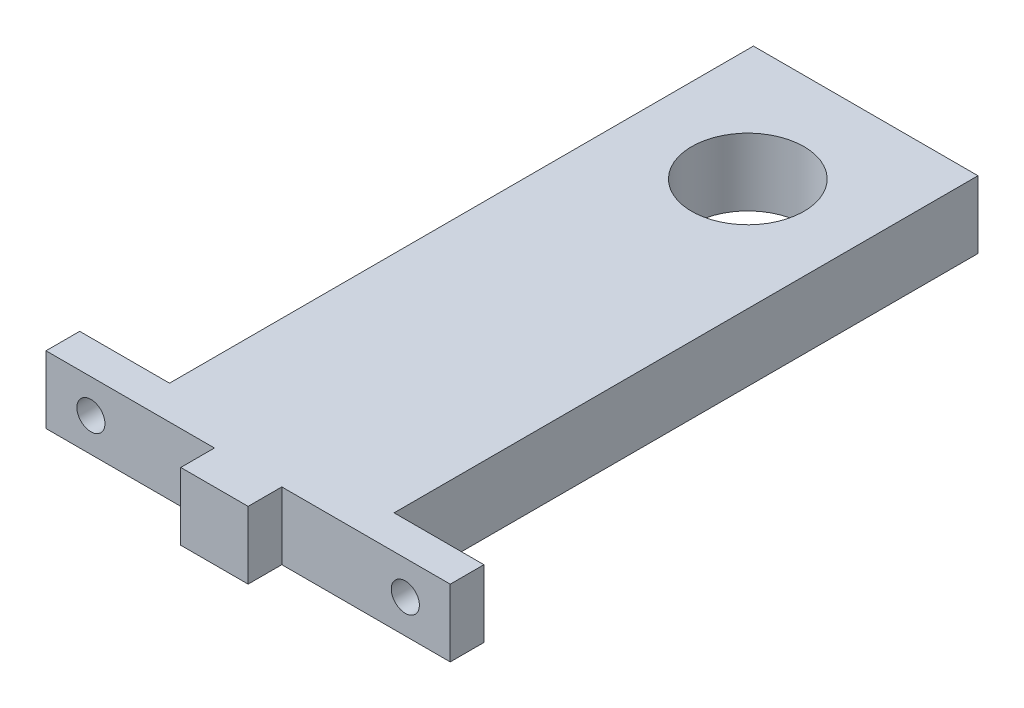
SolidWorks part; units mm, degrees
ref_plane "前视基准面" through (0, 0, 0) normal (0, 0, 1) x (1, 0, 0)
ref_plane "上视基准面" through (0, 0, 0) normal (0, 1, 0) x (1, 0, 0)
ref_plane "右视基准面" through (0, 0, 0) normal (1, 0, 0) x (0, 0, -1)
sketch "草图1" plane through (0, 0, 0) normal (0, 1, 0) x (1, 0, 0)
  line L0 (0, 29.7437) -> (0, -35.8813) construction
  line L1 (-10, 37.3687) -> (10, 37.3687)
  line L2 (10, 37.3687) -> (10, -14.6313)
  line L3 (10, -14.6313) -> (18, -14.6313)
  line L4 (18, -14.6313) -> (18, -17.6313)
  line L5 (18, -17.6313) -> (3, -17.6313)
  line L6 (3, -17.6313) -> (3, -20.6313)
  line L7 (3, -20.6313) -> (-3, -20.6313)
  line L8 (-3, -17.6313) -> (-3, -20.6313)
  line L9 (-18, -17.6313) -> (-3, -17.6313)
  line L10 (-18, -14.6313) -> (-18, -17.6313)
  line L11 (-10, -14.6313) -> (-18, -14.6313)
  line L12 (-10, 37.3687) -> (-10, -14.6313)
  point P3 (0, 0)
  point P12 (0, -20.6313)
  point P17 (0, 37.3687)
  point P18 (0, 0)
  dimension "D1" = 3
  dimension "D2" = 3
  dimension "D3" = 52
  dimension "D4" = 3
  dimension "D5" = 10
  dimension "D6" = 18
extrude "凸台-拉伸1" add sketch "草图1" along normal blind 6
sketch "草图3" plane through (0, 0, 0) normal (0, -1, 0) x (1, 0, 0)
  line L0 (0, -37.3687) -> (0, 20.6313) construction
  line L1 (10, -37.3687) -> (-10, -37.3687) construction
  line L2 (-3, 20.6313) -> (3, 20.6313) construction
  line L3 (3, 17.6313) -> (18, 17.6313) construction
  circle A0 centre (0, -26.8687) radius 5
  dimension "D1" = 44.5
extrude "切除-拉伸1" cut sketch "草图3" against normal through all
sketch "草图4" plane through (0, 0, 0) normal (0, 0, 1) x (1, 0, 0)
  line L0 (-18, 3) -> (18, 3) construction
  line L1 (-18, 6) -> (-18, 0) construction
  line L2 (18, 6) -> (18, 0) construction
  line L3 (0, 6) -> (0, 0) construction
  line L4 (-3, 6) -> (3, 6) construction
  circle A0 centre (-14, 3) radius 1.25
  circle A1 centre (14, 3) radius 1.25
  dimension "D1" = 28
extrude "切除-拉伸3" cut sketch "草图4" against normal through all both and the other way through all
